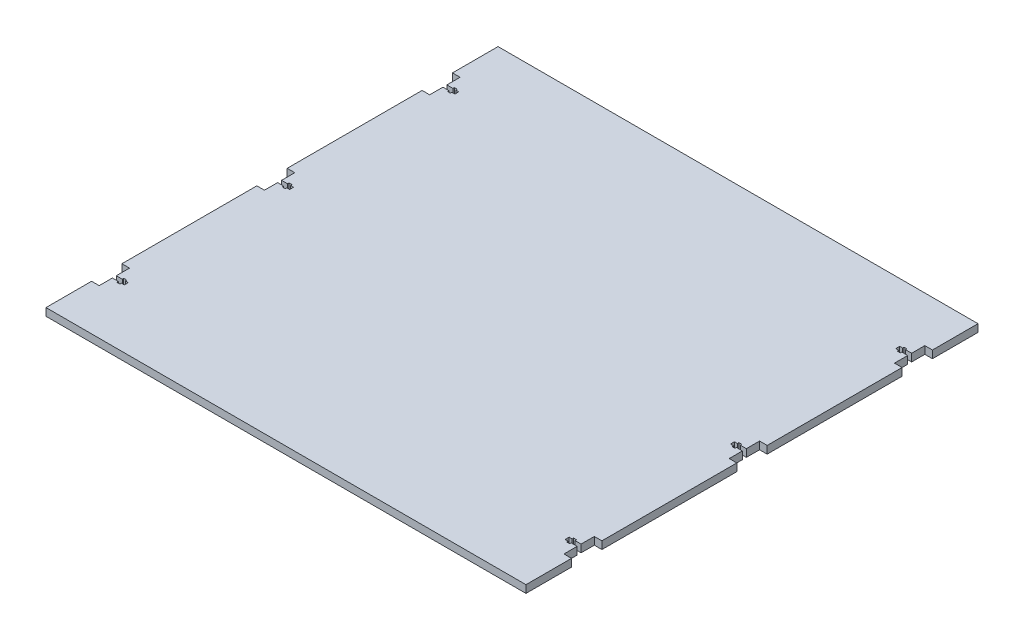
SolidWorks part; units mm, degrees
material "Pine"
ref_plane "Front Plane" through (0, 0, 0) normal (0, 0, 1) x (1, 0, 0)
ref_plane "Top Plane" through (0, 0, 0) normal (0, 1, 0) x (1, 0, 0)
ref_plane "Right Plane" through (0, 0, 0) normal (1, 0, 0) x (0, 0, -1)
ref_plane "Plane1" through (0, 72.8285, -271.7998) normal (0, 0.2588, -0.9659) x (-1, 0, 0)
sketch "Sketch1" plane through (0, 0, -215.9165) normal (0, 1, 0) x (-1, 0, 0)
  line L0 (1.15, 250.6332) -> (-1.35, 250.6332)
  line L1 (-1.35, 250.6332) -> (-1.35, 251.8332)
  line L2 (-1.35, 251.8332) -> (-6.35, 251.8332)
  line L3 (-6.35, 251.8332) -> (-6.35, 240.7832)
  line L4 (-6.35, 240.7832) -> (-12.7, 240.7832)
  line L5 (-12.7, 240.7832) -> (-12.7, 127.9935)
  line L6 (-12.7, 127.9935) -> (-6.35, 127.9935)
  line L7 (-6.35, 127.9935) -> (-6.35, 116.9435)
  line L8 (-6.35, 116.9435) -> (-1.35, 116.9435)
  line L9 (-1.35, 116.9435) -> (-1.35, 118.1435)
  line L10 (-1.35, 118.1435) -> (1.15, 118.1435)
  line L11 (1.15, 118.1435) -> (1.15, 116.9435)
  line L12 (1.15, 116.9435) -> (3.65, 116.9435)
  line L13 (3.65, 116.9435) -> (3.65, 113.6435)
  line L14 (3.65, 113.6435) -> (1.15, 113.6435)
  line L15 (1.15, 113.6435) -> (1.15, 112.4435)
  line L16 (1.15, 112.4435) -> (-1.35, 112.4435)
  line L17 (-1.35, 112.4435) -> (-1.35, 113.6435)
  line L18 (-1.35, 113.6435) -> (-6.35, 113.6435)
  line L19 (-6.35, 113.6435) -> (-6.35, 102.5935)
  line L20 (-6.35, 102.5935) -> (-12.7, 102.5935)
  line L21 (-12.7, 102.5935) -> (-12.7, -10.1962)
  line L22 (-12.7, -10.1962) -> (-6.35, -10.1962)
  line L23 (-6.35, -10.1962) -> (-6.35, -21.2462)
  line L24 (-6.35, -21.2462) -> (-1.35, -21.2462)
  line L25 (-1.35, -21.2462) -> (-1.35, -20.0462)
  line L26 (-1.35, -20.0462) -> (1.15, -20.0462)
  line L27 (1.15, -20.0462) -> (1.15, -21.2462)
  line L28 (1.15, -21.2462) -> (3.65, -21.2462)
  line L29 (3.65, -21.2462) -> (3.65, -24.5462)
  line L30 (3.65, -24.5462) -> (1.15, -24.5462)
  line L31 (1.15, -24.5462) -> (1.15, -25.7462)
  line L32 (1.15, -25.7462) -> (-1.35, -25.7462)
  line L33 (-1.35, -25.7462) -> (-1.35, -24.5462)
  line L34 (-1.35, -24.5462) -> (-6.35, -24.5462)
  line L35 (-6.35, -24.5462) -> (-6.35, -35.5962)
  line L36 (-6.35, -35.5962) -> (-12.7, -35.5962)
  line L37 (-12.7, -35.5962) -> (-12.7, -73.6962)
  line L38 (-12.7, -73.6962) -> (388.62, -73.6962)
  line L39 (388.62, -73.6962) -> (388.62, -35.5962)
  line L40 (388.62, -35.5962) -> (382.27, -35.5962)
  line L41 (382.27, -35.5962) -> (382.27, -24.5462)
  line L42 (382.27, -24.5462) -> (377.27, -24.5462)
  line L43 (377.27, -24.5462) -> (377.27, -25.7462)
  line L44 (377.27, -25.7462) -> (374.77, -25.7462)
  line L45 (374.77, -25.7462) -> (374.77, -24.5462)
  line L46 (374.77, -24.5462) -> (372.27, -24.5462)
  line L47 (372.27, -24.5462) -> (372.27, -21.2462)
  line L48 (372.27, -21.2462) -> (374.77, -21.2462)
  line L49 (374.77, -21.2462) -> (374.77, -20.0462)
  line L50 (374.77, -20.0462) -> (377.27, -20.0462)
  line L51 (377.27, -20.0462) -> (377.27, -21.2462)
  line L52 (377.27, -21.2462) -> (382.27, -21.2462)
  line L53 (382.27, -21.2462) -> (382.27, -10.1962)
  line L54 (382.27, -10.1962) -> (388.62, -10.1962)
  line L55 (388.62, -10.1962) -> (388.62, 102.5935)
  line L56 (388.62, 102.5935) -> (382.27, 102.5935)
  line L57 (382.27, 102.5935) -> (382.27, 113.6435)
  line L58 (382.27, 113.6435) -> (377.27, 113.6435)
  line L59 (377.27, 113.6435) -> (377.27, 112.4435)
  line L60 (377.27, 112.4435) -> (374.77, 112.4435)
  line L61 (374.77, 112.4435) -> (374.77, 113.6435)
  line L62 (374.77, 113.6435) -> (372.27, 113.6435)
  line L63 (372.27, 113.6435) -> (372.27, 116.9435)
  line L64 (372.27, 116.9435) -> (374.77, 116.9435)
  line L65 (374.77, 116.9435) -> (374.77, 118.1435)
  line L66 (374.77, 118.1435) -> (377.27, 118.1435)
  line L67 (377.27, 118.1435) -> (377.27, 116.9435)
  line L68 (377.27, 116.9435) -> (382.27, 116.9435)
  line L69 (382.27, 116.9435) -> (382.27, 127.9935)
  line L70 (382.27, 127.9935) -> (388.62, 127.9935)
  line L71 (388.62, 127.9935) -> (388.62, 240.7832)
  line L72 (388.62, 240.7832) -> (382.27, 240.7832)
  line L73 (382.27, 240.7832) -> (382.27, 251.8332)
  line L74 (382.27, 251.8332) -> (377.27, 251.8332)
  line L75 (377.27, 251.8332) -> (377.27, 250.6332)
  line L76 (377.27, 250.6332) -> (374.77, 250.6332)
  line L77 (374.77, 250.6332) -> (374.77, 251.8332)
  line L78 (374.77, 251.8332) -> (372.27, 251.8332)
  line L79 (372.27, 251.8332) -> (372.27, 255.1332)
  line L80 (372.27, 255.1332) -> (374.77, 255.1332)
  line L81 (374.77, 255.1332) -> (374.77, 256.3332)
  line L82 (374.77, 256.3332) -> (377.27, 256.3332)
  line L83 (377.27, 256.3332) -> (377.27, 255.1332)
  line L84 (377.27, 255.1332) -> (382.27, 255.1332)
  line L85 (382.27, 255.1332) -> (382.27, 266.1832)
  line L86 (382.27, 266.1832) -> (388.62, 266.1832)
  line L87 (388.62, 266.1832) -> (388.62, 304.2832)
  line L88 (388.62, 304.2832) -> (-12.7, 304.2832)
  line L89 (-12.7, 304.2832) -> (-12.7, 266.1832)
  line L90 (-12.7, 266.1832) -> (-6.35, 266.1832)
  line L91 (-6.35, 266.1832) -> (-6.35, 255.1332)
  line L92 (-6.35, 255.1332) -> (-1.35, 255.1332)
  line L93 (-1.35, 255.1332) -> (-1.35, 256.3332)
  line L94 (-1.35, 256.3332) -> (1.15, 256.3332)
  line L95 (1.15, 256.3332) -> (1.15, 255.1332)
  line L96 (1.15, 255.1332) -> (3.65, 255.1332)
  line L97 (3.65, 255.1332) -> (3.65, 251.8332)
  line L98 (3.65, 251.8332) -> (1.15, 251.8332)
  line L99 (1.15, 251.8332) -> (1.15, 250.6332)
extrude "Boss-Extrude1" add sketch "Sketch1" against normal blind 6.35
